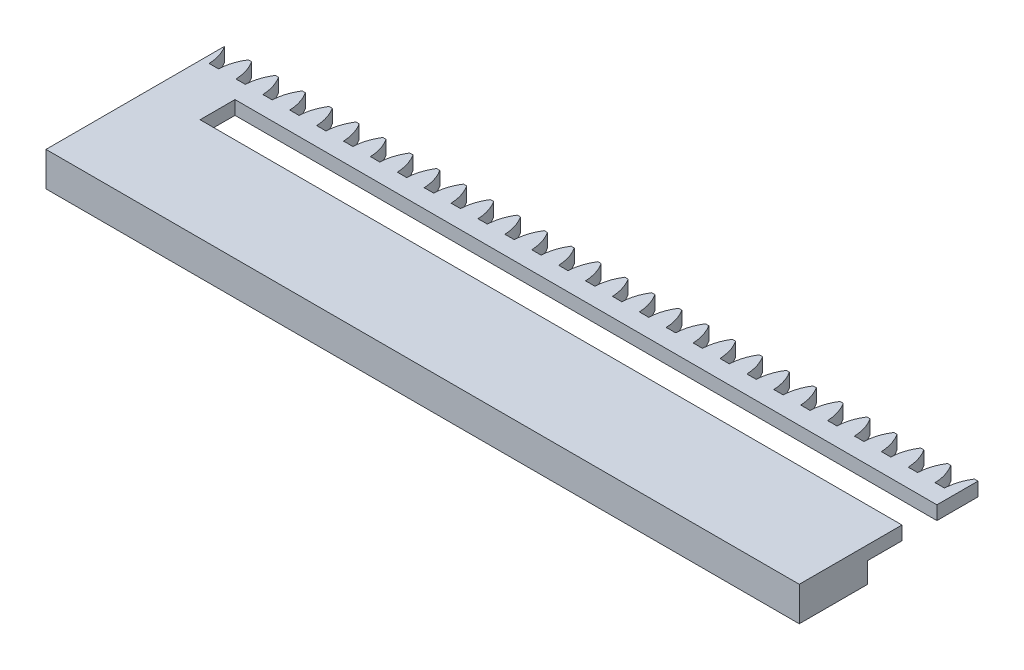
SolidWorks part; units mm, degrees
ref_plane "Front Plane" through (0, 0, 0) normal (0, 0, 1) x (1, 0, 0)
ref_plane "Top Plane" through (0, 0, 0) normal (0, 1, 0) x (1, 0, 0)
ref_plane "Right Plane" through (0, 0, 0) normal (1, 0, 0) x (0, 0, -1)
sketch "Sketch1" plane through (0, 0, 0) normal (0, 1, 0) x (1, 0, 0)
  line L0 (-149.225, -38.1) -> (-149.225, 28.194)
  line L1 (-130.175, 12.954) -> (130.175, 12.954)
  line L3 (-149.225, 28.194) -> (130.175, 28.194)
  line L4 (130.175, 12.954) -> (130.175, 28.194)
  line L5 (-130.175, 0) -> (130.175, 0)
  line L7 (-149.225, -38.1) -> (130.175, -38.1)
  line L8 (130.175, 0) -> (130.175, -38.1)
  line L12 (-130.175, 0) -> (-130.175, 12.954)
  point P11 (0, 0)
  dimension "D1" = 279.4
  dimension "D3" = 12.954
  dimension "D5" = 38.1
  dimension "D4" = 19.05
  dimension "D2" = 15.24
extrude "Boss-Extrude1" add sketch "Sketch1" along normal blind 5.08
sketch "Sketch2" plane through (0, 5.08, 0) normal (0, 1, 0) x (1, 0, 0)
  line L0 (-146.57, 19.717) -> (-144.8366, -26.6056) construction
  line L1 (-144.8366, 28.194) -> (-144.8366, -26.6056) construction
  line L2 (-147.3302, 24.1332) -> (-142.343, 24.1332) construction
  line L3 (-149.6736, 30.5718) -> (-144.8366, 17.2821) construction
  line L4 (130.175, 28.194) -> (-149.225, 28.194) construction
  arc A0 (-146.57, 19.717) -> (-149.225, 28.194) centre (-163.4465, 19.0855) ccw
  circle A1 centre (-144.8366, -26.6056) radius 50.8 construction
  arc A2 (-143.1032, 19.717) -> (-140.4481, 28.194) centre (-126.2266, 19.0855) cw
  circle A3 centre (-144.8366, -26.6056) radius 53.975 construction
  arc A4 (-143.1032, 19.717) -> (-146.57, 19.717) centre (-144.8366, -26.6056) ccw
  arc A5 (-140.4481, 28.194) -> (-149.225, 28.194) centre (-144.8366, -26.6056) ccw
  dimension "D1" = 101.6
  dimension "D2" = 107.95
  dimension "D3" = 7.62
  dimension "D4" = 1
  dimension "D5" = 20
  dimension "D6" = 4.9872
extrude "Cut-Extrude1" cut sketch "Sketch2" against normal through all
pattern_linear "LPattern1" count 28 spacing 9.9743 along (1, 0, 0) of "Cut-Extrude1"
sketch "Sketch4" plane through (0, 0, 0) normal (0, -1, 0) x (1, 0, 0)
  line L0 (-149.225, -28.194) -> (-149.225, 38.1) construction
  line L1 (130.175, 38.1) -> (-149.225, 38.1)
  line L2 (130.175, 38.1) -> (130.175, 12.7)
  line L3 (130.175, 12.7) -> (-149.225, 12.7)
  line L4 (-149.225, 38.1) -> (-149.225, 12.7)
  dimension "D1" = 25.4
extrude "Boss-Extrude2" add sketch "Sketch4" along normal blind 7.62
equation "\"Circular Pitch\"= 0.39269in"
equation "\"Pressure\"= 20deg"
equation "\"Root Diameter\"= 4in"
equation "\"Module\"= 0.125"
equation "\"Number of Teeth\"= 32"
equation "\"D1@Sketch2\"=\"Module\"*\"Number of Teeth\""
equation "\"D3@Sketch2\"=\"Module\"*if(\"Module\"=>1.25,2.25,2.4)"
equation "\"D5@Sketch2\"=\"Pressure\""
equation "\"D6@Sketch2\"=\"Circular Pitch\"/2"
equation "\"Length\"= 11"
equation "\"D1@Sketch1\"=\"Length\""
equation "\"D3@LPattern1\"=\"Circular Pitch\""
equation "\"D1@LPattern1\"=INT(\"Length\"/\"Circular Pitch\")"
